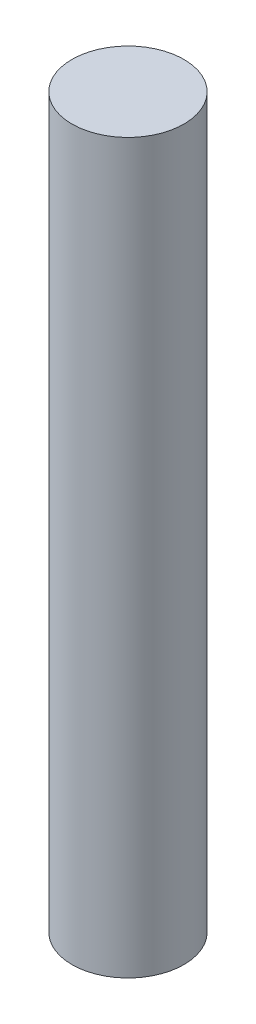
SolidWorks part; units mm, degrees
material "Custom Plastic"
ref_plane "Front Plane" through (0, 0, 0) normal (0, 0, 1) x (1, 0, 0)
ref_plane "Top Plane" through (0, 0, 0) normal (0, 1, 0) x (1, 0, 0)
ref_plane "Right Plane" through (0, 0, 0) normal (1, 0, 0) x (0, 0, -1)
sketch "Sketch1" plane through (0, 0, 0) normal (0, 1, 0) x (1, 0, 0)
  circle A0 centre (0, 0) radius 20
  dimension "D1" = 40
extrude "Boss-Extrude1" add sketch "Sketch1" along normal blind 260
scale "Scale1" scale about centroid uniform scaling yes scale factor 0.75
